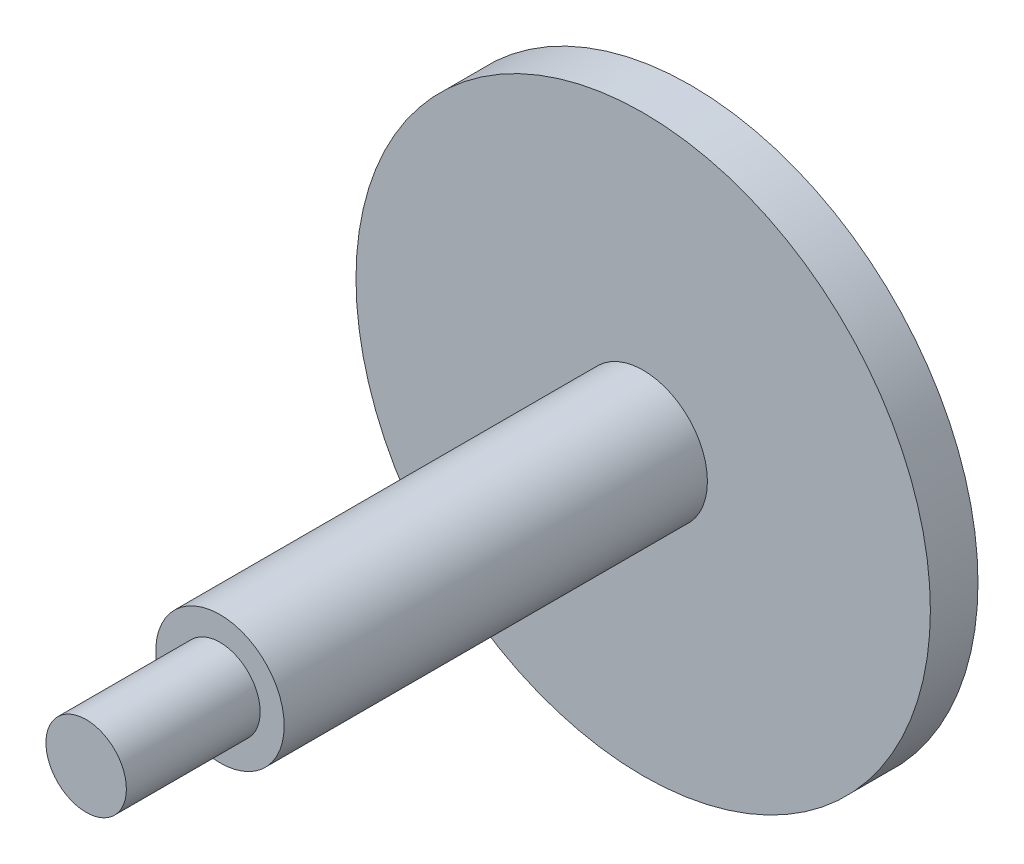
SolidWorks part; units mm, degrees
ref_plane "Front Plane" through (0, 0, 0) normal (0, 0, 1) x (1, 0, 0)
ref_plane "Top Plane" through (0, 0, 0) normal (0, 1, 0) x (1, 0, 0)
ref_plane "Right Plane" through (0, 0, 0) normal (1, 0, 0) x (0, 0, -1)
sketch "Sketch1" plane through (0, 0, 0) normal (0, 0, 1) x (1, 0, 0)
  circle A0 centre (0, 0) radius 60.325
  dimension "D1" = 120.65
extrude "Boss-Extrude1" add sketch "Sketch1" along normal blind 10
sketch "Sketch2" plane through (0, 0, 10) normal (0, 0, 1) x (1, 0, 0)
  circle A0 centre (0, 0) radius 13.4937
  circle A1 centre (0, 0) radius 60.325
  circle A2 centre (0, 0) radius 60.325
  dimension "D2" = 26.9875
  dimension "D1" = 0
extrude "Boss-Extrude2" add sketch "Sketch2" along normal blind 117 contours A0
sketch "Sketch3" plane through (0, 0, 127) normal (0, 0, 1) x (1, 0, 0)
  circle A1 centre (0, 0) radius 13.4937
  circle A2 centre (0, 0) radius 13.4937
  dimension "D1" = 0
extrude "Cut-Extrude1" cut sketch "Sketch3" against normal blind 28.1
sketch "Sketch4" plane through (0, 0, 98.9) normal (0, 0, 1) x (1, 0, 0)
  circle A0 centre (0, 0) radius 8.4491
  circle A1 centre (0, 0) radius 13.4937
  circle A2 centre (0, 0) radius 13.4937
  dimension "D1" = 0
extrude "Boss-Extrude3" add sketch "Sketch4" along normal blind 28.1 contours A0
